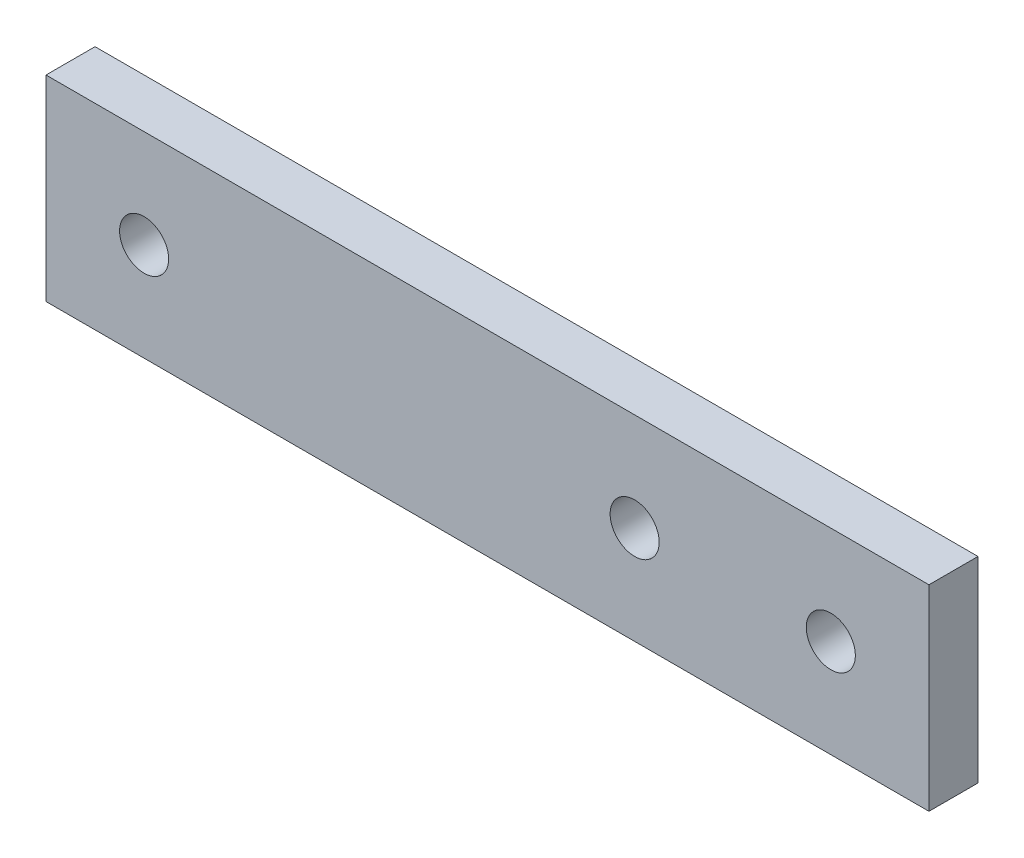
SolidWorks part; units mm, degrees
ref_plane "Front Plane" through (0, 0, 0) normal (0, 0, 1) x (1, 0, 0)
ref_plane "Top Plane" through (0, 0, 0) normal (0, 1, 0) x (1, 0, 0)
ref_plane "Right Plane" through (0, 0, 0) normal (1, 0, 0) x (0, 0, -1)
sketch "Sketch1" plane through (0, 0, 0) normal (1, 0, 0) x (0, 0, -1)
  line L1 (0, 0) -> (-6.35, 0)
  line L2 (0, 0) -> (0, 25.4)
  line L3 (0, 25.4) -> (-6.35, 25.4)
  line L4 (-6.35, 0) -> (-6.35, 25.4)
  dimension "D1" = 25.4
  dimension "D2" = 6.35
extrude "Boss-Extrude1" add sketch "Sketch1" along normal blind 114.3
sketch "Sketch2" plane through (0, 0, 6.35) normal (0, 0, 1) x (1, 0, 0)
  line L0 (114.3, 12.7) -> (101.6, 12.7) construction
  line L1 (114.3, 25.4) -> (114.3, 0) construction
  line L2 (101.6, 12.7) -> (76.2, 12.7) construction
  line L3 (76.2, 12.7) -> (12.7, 12.7) construction
  line L5 (12.7, 12.7) -> (0, 12.7) construction
  line L6 (0, 25.4) -> (0, 0) construction
  circle A0 centre (12.7, 12.7) radius 3.175
  circle A1 centre (76.2, 12.7) radius 3.175
  circle A2 centre (101.6, 12.7) radius 3.175
  dimension "D4" = 6.35
  dimension "D1" = 12.7
  dimension "D2" = 25.4
extrude "Cut-Extrude1" cut sketch "Sketch2" against normal through all
